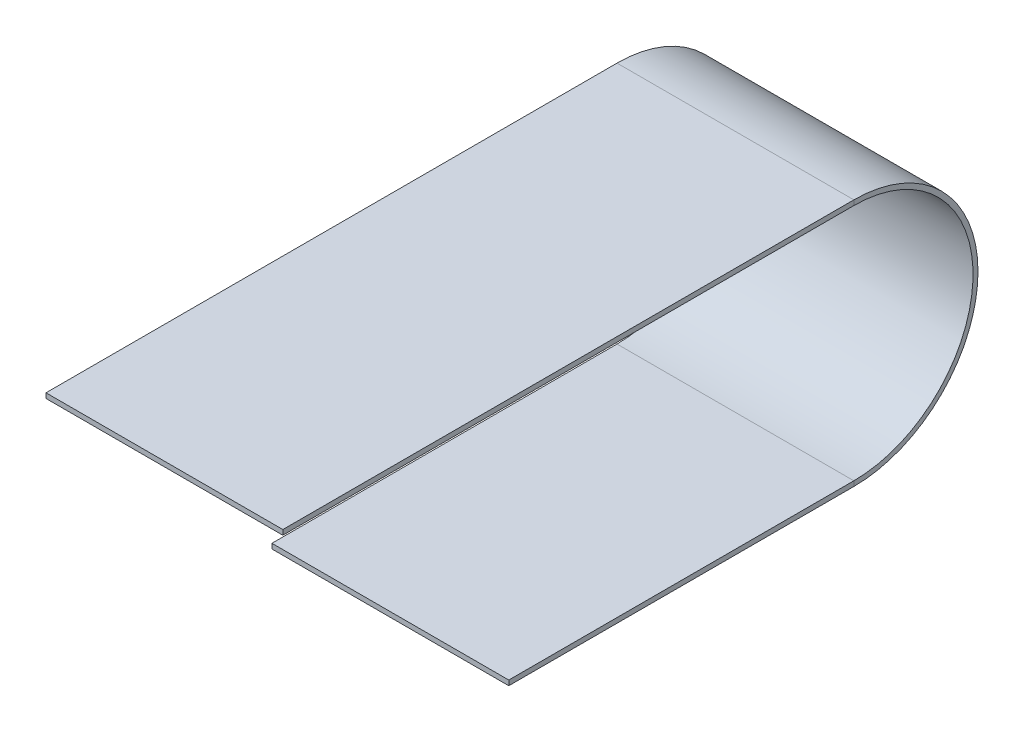
SolidWorks part; units mm, degrees
ref_plane "정면" through (0, 0, 0) normal (0, 0, 1) x (1, 0, 0)
ref_plane "윗면" through (0, 0, 0) normal (0, 1, 0) x (1, 0, 0)
ref_plane "우측면" through (0, 0, 0) normal (1, 0, 0) x (0, 0, -1)
sketch "스케치1" plane through (0, 0, -8.8) normal (0, 0, -1) x (-1, 0, 0)
  line L4 (-15.23, 0) -> (-24.77, 0)
  line L5 (-24.77, 0) -> (-24.77, -0.2)
  line L6 (-24.77, -0.2) -> (-15.23, -0.2)
  line L7 (-15.23, -0.2) -> (-15.23, 0)
  line L8 (-15.23, 0) -> (-24.77, 0)
  line L9 (-24.77, 0) -> (-24.77, -0.2)
  line L10 (-24.77, -0.2) -> (-15.23, -0.2)
  line L11 (-15.23, -0.2) -> (-15.23, 0)
  point P2 (-20, 0)
  dimension "D1" = 0
ref_plane "평면1" through (20, 0, 0) normal (1, 0, 0) x (0, 0, -1)
sketch "스케치3" plane through (20, 0, 0) normal (1, 0, 0) x (0, 0, -1)
  line L0 (8.8, 0) -> (31.8, 0)
  line L1 (31.8, -10) -> (17.9, -10)
  arc A0 (31.8, 0) -> (31.8, -10) centre (31.8, -5) cw
  dimension "D1" = 10
  dimension "D2" = 23
  dimension "D3" = 9.1
sweep "스윕1" add profiles "스케치1" path "스케치3"
